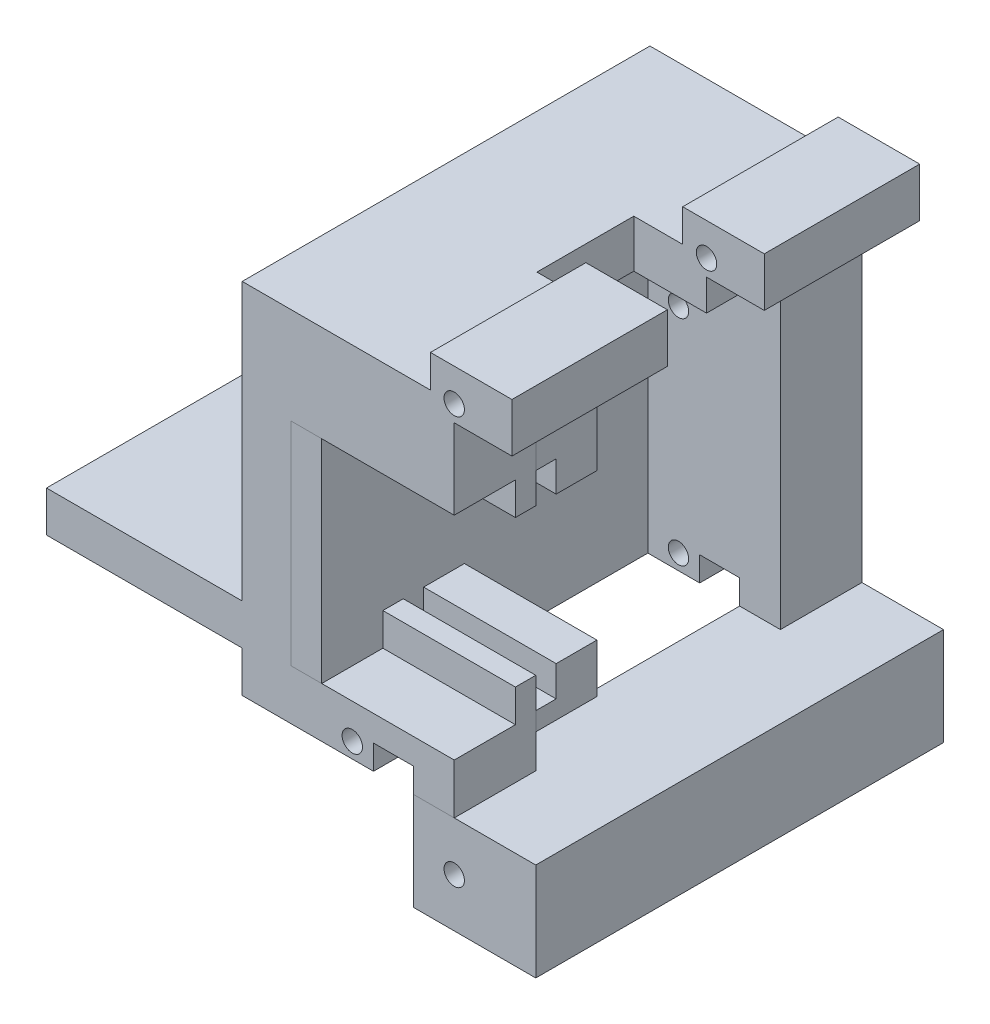
SolidWorks part; units mm, degrees
material "ABS"
ref_plane "Front Plane" through (0, 0, 0) normal (0, 0, 1) x (1, 0, 0)
ref_plane "Top Plane" through (0, 0, 0) normal (0, 1, 0) x (1, 0, 0)
ref_plane "Right Plane" through (0, 0, 0) normal (1, 0, 0) x (0, 0, -1)
sketch "Sketch8" plane through (0, 0, 0) normal (0, 0, 1) x (1, 0, 0)
  line L0 (0, 0) -> (0, 48.6918)
  line L1 (0, 48.6918) -> (-33.02, 48.6918)
  line L2 (-33.02, 48.6918) -> (-33.02, 5.588)
  line L3 (-33.02, 5.588) -> (-63.5, 5.588)
  line L4 (-63.5, 5.588) -> (-63.5, -0.762)
  line L5 (-63.5, -0.762) -> (-33.02, -0.762)
  line L6 (-33.02, -0.762) -> (-33.02, -9.525)
  line L8 (-33.02, -9.525) -> (-9.525, -9.525)
  line L11 (0, 0) -> (0, -9.525)
  line L12 (0, -9.525) -> (-9.525, -9.525)
  line L13 (-15.875, -4.7625) -> (-15.875, 28.5877) construction
  circle A0 centre (-15.875, 28.5877) radius 1.5875
  circle A1 centre (-15.875, -4.7625) radius 1.5875
  dimension "D7" = 3.175
  dimension "D8" = 15.875
  dimension "D9" = 3.175
  dimension "D1" = 30.48
  dimension "D2" = 33.02
  dimension "D3" = 48.6918
  dimension "D4" = 43.1038
  dimension "D5" = 6.35
  dimension "D6" = 23.495
extrude "Boss-Extrude3" add sketch "Sketch8" along normal blind 101.6
sketch "Sketch40" plane through (0, -9.525, 0) normal (0, -1, 0) x (1, 0, 0)
  line L0 (0, 0) -> (0, 31.75) construction
  line L1 (0, 101.6) -> (0, 0) construction
  line L2 (0, 31.75) -> (-25.4, 31.75)
  line L3 (-25.4, 31.75) -> (-25.4, 69.85)
  line L4 (-25.4, 69.85) -> (0, 69.85)
  line L5 (0, 69.85) -> (0, 31.75)
extrude "Cut-Extrude24" cut sketch "Sketch40" against normal blind 50.8
sketch "Sketch18" plane through (0, 0, 101.6) normal (0, 0, 1) x (1, 0, 0)
  line L0 (-33.02, -9.525) -> (-33.02, -7.1628)
  line L1 (-33.02, -0.762) -> (-33.02, -9.525) construction
  line L3 (-33.02, -7.1628) -> (0, -7.1628)
  line L4 (0, 48.6918) -> (0, -9.525) construction
  line L5 (0, -7.1628) -> (0, -9.525)
  line L6 (0, -9.525) -> (-33.02, -9.525)
extrude "Cut-Extrude11" cut sketch "Sketch18" against normal blind 101.6 and the other way through all
sketch "Sketch19" plane through (0, 0, 0) normal (0, 0, -1) x (-1, 0, 0)
  line L0 (3.7065, 48.6918) -> (3.7065, 53.7718)
  line L1 (0, 48.6918) -> (33.02, 48.6918) construction
  line L2 (3.7065, 53.7718) -> (-8.9935, 53.7718)
  line L3 (-8.9935, 53.7718) -> (-8.9935, 46.1359)
  line L6 (-8.9935, 46.1359) -> (0, 46.1359)
  circle A0 centre (15.875, -4.7625) radius 1.5875 construction
  circle A1 centre (0, 48.6918) radius 1.5875
  point P0 (14.2879, -4.7289)
  point P1 (14.2879, -4.7961)
  point P4 (15.875, -4.7625)
  dimension "D1" = 3.175
  dimension "D2" = 5.08
sketch "Sketch20" plane through (0, 0, 101.6) normal (0, 0, 1) x (1, 0, 0)
  circle A0 centre (0, 48.6918) radius 1.5875
  dimension "D1" = 3.175
extrude "Boss-Extrude4" add sketch "Sketch19" against normal blind 101.6
extrude "Cut-Extrude12" cut sketch "Sketch20" against normal blind 101.6
sketch "Sketch21" plane through (0, -7.1628, 0) normal (0, -1, 0) x (1, 0, 0)
  line L28 (-33.02, 101.6) -> (0, 101.6)
  line L29 (0, 101.6) -> (0, 82.55)
  line L30 (0, 101.6) -> (0, 69.85) construction
  line L31 (0, 82.55) -> (-33.02, 82.55)
  line L32 (-33.02, 101.6) -> (-33.02, 0) construction
  line L33 (-33.02, 82.55) -> (-33.02, 101.6)
  line L34 (-33.02, 0) -> (-33.02, 19.05)
  line L35 (-33.02, 19.05) -> (0, 19.05)
  line L36 (0, 31.75) -> (0, 0) construction
  line L37 (0, 19.05) -> (0, 0)
  line L38 (0, 0) -> (-33.02, 0)
extrude "Cut-Extrude13" cut sketch "Sketch21" against normal through all
sketch "Sketch24" plane through (0, 53.7718, 0) normal (0, 1, 0) x (1, 0, 0)
  line L11 (8.9935, -101.6) -> (8.9935, 0) construction
  line L20 (0, -82.55) -> (8.9935, -82.55)
  line L21 (8.9935, -82.55) -> (8.9935, -101.6)
  line L22 (8.9935, -101.6) -> (0, -101.6)
  line L23 (0, -101.6) -> (0, -82.55)
  line L24 (0, 0) -> (8.9935, 0)
  line L25 (8.9935, 0) -> (8.9935, -19.05)
  line L26 (8.9935, -19.05) -> (0, -19.05)
  line L27 (0, -19.05) -> (0, 0)
extrude "Cut-Extrude15" cut sketch "Sketch24" against normal through all
sketch "Sketch38" plane through (8.9935, 0, 0) normal (1, 0, 0) x (0, 0, -1)
  line L10 (-50.8, 53.7718) -> (-43.2562, 53.7718) construction
  line L12 (-43.2562, 53.7718) -> (-58.3438, 53.7718)
  line L16 (-58.3438, 53.7718) -> (-58.3438, 46.1359)
  line L18 (-82.55, 46.1359) -> (-19.05, 46.1359) construction
  line L20 (-82.55, 53.7718) -> (-19.05, 53.7718) construction
  line L25 (-58.3438, 46.1359) -> (-43.2562, 46.1359)
  line L26 (-43.2562, 46.1359) -> (-43.2562, 53.7718)
extrude "Cut-Extrude21" cut sketch "Sketch38" against normal blind 20.32
sketch "Sketch41" plane through (0, 5.588, 0) normal (0, 1, 0) x (1, 0, 0)
  line L9 (-63.5, 0) -> (-33.02, 0)
  line L10 (-33.02, 0) -> (-33.02, -19.05)
  line L11 (-33.02, -19.05) -> (-33.02, 0) construction
  line L12 (-33.02, -19.05) -> (-63.5, -19.05)
  line L13 (-63.5, -101.6) -> (-63.5, 0) construction
  line L14 (-63.5, -19.05) -> (-63.5, 0)
  line L15 (-33.02, -101.6) -> (-63.5, -101.6)
  line L16 (-63.5, -101.6) -> (-63.5, -82.55)
  line L17 (-63.5, -82.55) -> (-33.02, -82.55)
  line L18 (-33.02, -82.55) -> (-33.02, -19.05) construction
  line L19 (-33.02, -101.6) -> (-33.02, -82.55) construction
  line L20 (-33.02, -82.55) -> (-33.02, -101.6)
extrude "Cut-Extrude25" cut sketch "Sketch41" against normal through all
sketch "Sketch42" plane through (0, 0, 69.85) normal (0, 0, -1) x (-1, 0, 0)
  line L0 (15.875, 28.5877) -> (15.875, 33.6677) construction
  line L1 (15.875, 33.6677) -> (0, 33.6677) construction
  line L2 (0, 41.275) -> (0, -7.1628) construction
sketch "Sketch43" plane through (0, 0, 0) normal (1, 0, 0) x (0, 0, -1)
  line L6 (-69.85, 33.6677) -> (-69.85, 0.6477)
  line L7 (-69.85, 41.275) -> (-69.85, -7.1628) construction
  line L8 (-69.85, 0.6477) -> (-82.55, 0.6477)
  line L9 (-82.55, 46.1359) -> (-82.55, -7.1628) construction
  line L10 (-82.55, 0.6477) -> (-82.55, 33.6677)
  line L11 (-82.55, 33.6677) -> (-69.85, 33.6677)
extrude "Cut-Extrude26" cut sketch "Sketch43" against normal blind 25.4
sketch "Sketch44" plane through (-25.4, 0, 0) normal (1, 0, 0) x (0, 0, -1)
  line L11 (-69.85, 33.6677) -> (-73.025, 33.6677)
  line L12 (-69.85, 33.6677) -> (-82.55, 33.6677) construction
  line L13 (-73.025, 33.6677) -> (-73.025, 28.5877)
  line L14 (-73.025, 28.5877) -> (-69.85, 28.5877)
  line L15 (-69.85, 0.6477) -> (-69.85, -7.1628) construction
  line L16 (-69.85, 28.5877) -> (-69.85, 33.6677)
  line L17 (-69.85, 0.6477) -> (-69.85, 5.7277)
  line L18 (-69.85, 5.7277) -> (-73.025, 5.7277)
  line L19 (-73.025, 5.7277) -> (-73.025, 0.6477)
  line L20 (-82.55, 0.6477) -> (-69.85, 0.6477) construction
  line L21 (-73.025, 0.6477) -> (-69.85, 0.6477)
extrude "Boss-Extrude5" add sketch "Sketch44" along normal blind 25.4
sketch "Sketch45" plane through (-25.4, 0, 0) normal (1, 0, 0) x (0, 0, -1)
  line L1 (-69.85, 41.275) -> (-31.75, 41.275) construction
  line L4 (-69.85, 41.275) -> (-69.85, 28.5877) construction
  line L7 (-60.325, 5.715) -> (-60.325, -1.905)
  line L8 (-60.325, -1.905) -> (-69.85, -1.905)
  line L14 (-60.325, 5.715) -> (-66.675, 5.715)
  line L15 (-66.675, 5.715) -> (-66.675, 0.9525)
  line L16 (-66.675, 0.9525) -> (-69.85, 0.9525)
  line L17 (-69.85, 0.9525) -> (-69.85, -1.905)
  line L19 (-31.75, -7.1628) -> (-69.85, -7.1628) construction
  line L21 (-69.85, 41.275) -> (-60.325, 41.275)
  line L22 (-60.325, 41.275) -> (-60.325, 28.575)
  line L24 (-69.85, 28.575) -> (-69.85, 41.275)
  line L25 (-60.325, 28.575) -> (-66.675, 28.575)
  line L26 (-66.675, 28.575) -> (-66.675, 33.3375)
  line L27 (-66.675, 33.3375) -> (-69.85, 33.3375)
  dimension "D3" = 5.2578
  dimension "D4" = 8.1153
  dimension "D5" = 12.8778
extrude "Boss-Extrude6" add sketch "Sketch45" along normal blind 25.4 separate body
sketch "Sketch46" plane through (0, 0, 82.55) normal (0, 0, 1) x (1, 0, 0)
  line L0 (0, 48.6918) -> (0, -14.8082) construction
  line L1 (0, -7.1628) -> (12.7, -7.1628)
  line L2 (12.7, -7.1628) -> (12.7, -22.4028)
  line L3 (12.7, -22.4028) -> (-6.35, -22.4028)
  line L4 (-6.35, -22.4028) -> (-6.35, -7.1628)
  line L6 (-33.02, -7.1628) -> (0, -7.1628) construction
  circle A0 centre (0, -14.8082) radius 1.5875
extrude "Boss-Extrude7" add sketch "Sketch46" against normal blind 63.5 separate body
sketch "Sketch48" plane through (0, 0, 82.55) normal (0, 0, 1) x (1, 0, 0)
  line L0 (-12.573, -7.1628) -> (-12.573, -3.3468)
  line L1 (-33.02, -7.1628) -> (0, -7.1628) construction
  line L2 (-12.573, -3.3468) -> (-6.35, -3.3468)
  line L3 (-6.35, -3.3468) -> (-6.35, -7.1628)
  circle A0 centre (-15.875, -4.7625) radius 1.5875 construction
  dimension "D1" = 3.302
extrude "Cut-Extrude29" cut sketch "Sketch48" against normal blind 12.7 and the other way through all flip side to cut
sketch "Sketch49" plane through (0, 0, 19.05) normal (0, 0, -1) x (-1, 0, 0)
  line L0 (15.875, -4.7625) -> (12.573, -4.7625) construction
  line L1 (12.573, -7.1628) -> (12.573, -3.3528)
  line L2 (0, -7.1628) -> (33.02, -7.1628) construction
  line L3 (12.573, -3.3528) -> (6.35, -3.3528)
  line L4 (6.35, -3.3528) -> (6.35, -7.1628)
  line L5 (6.35, -7.1628) -> (12.573, -7.1628)
extrude "Cut-Extrude31" cut sketch "Sketch49" against normal blind 12.7
sketch "Sketch50" plane through (0, 46.1359, 0) normal (0, 1, 0) x (1, 0, 0)
  line L0 (0, -43.2562) -> (-11.3265, -43.2562)
  line L1 (-11.3265, -43.2562) -> (-11.3265, -58.3438)
  line L2 (-11.3265, -58.3438) -> (0, -58.3438)
  line L3 (0, -58.3438) -> (0, -43.2562)
extrude "Cut-Extrude33" cut sketch "Sketch50" against normal blind 4.8768
sketch "Sketch52" plane through (-25.4, 0, 0) normal (1, 0, 0) x (0, 0, -1)
  line L0 (-82.55, 33.6677) -> (-73.025, 33.6677)
  line L1 (-73.025, 33.6677) -> (-73.025, 28.5877)
  line L2 (-73.025, 28.5877) -> (-69.85, 28.5877)
  line L3 (-69.85, 28.5877) -> (-69.85, 33.3375)
  line L4 (-69.85, 33.3375) -> (-66.675, 33.3375)
  line L5 (-66.675, 33.3375) -> (-66.675, 28.5877)
  line L6 (-66.675, 28.5877) -> (-60.325, 28.575)
  line L7 (-60.325, 28.575) -> (-60.325, 41.275)
  line L8 (-60.325, 41.275) -> (-31.75, 41.275)
  line L9 (-31.75, 41.275) -> (-31.75, -7.1628)
  line L10 (-31.75, -7.1628) -> (-69.85, -7.1628)
  line L11 (-69.85, -7.1628) -> (-69.85, -1.905)
  line L12 (-69.85, -1.905) -> (-60.325, -1.905)
  line L13 (-60.325, -1.905) -> (-60.325, 5.715)
  line L14 (-60.325, 5.715) -> (-66.675, 5.715)
  line L15 (-66.675, 5.715) -> (-66.675, 0.9525)
  line L16 (-66.675, 0.9525) -> (-69.85, 0.9525)
  line L17 (-69.85, 0.9525) -> (-69.85, 5.7277)
  line L18 (-69.85, 5.7277) -> (-73.025, 5.7277)
  line L19 (-73.025, 5.7277) -> (-73.025, 0.6477)
  line L20 (-73.025, 0.6477) -> (-82.55, 0.6477)
  line L21 (-82.55, 0.6477) -> (-82.55, 33.6677)
  line L22 (-31.75, 30.1752) -> (-31.75, 27.0002) construction
extrude "Boss-Extrude8" add sketch "Sketch52" along normal blind 4.7625 separate body
